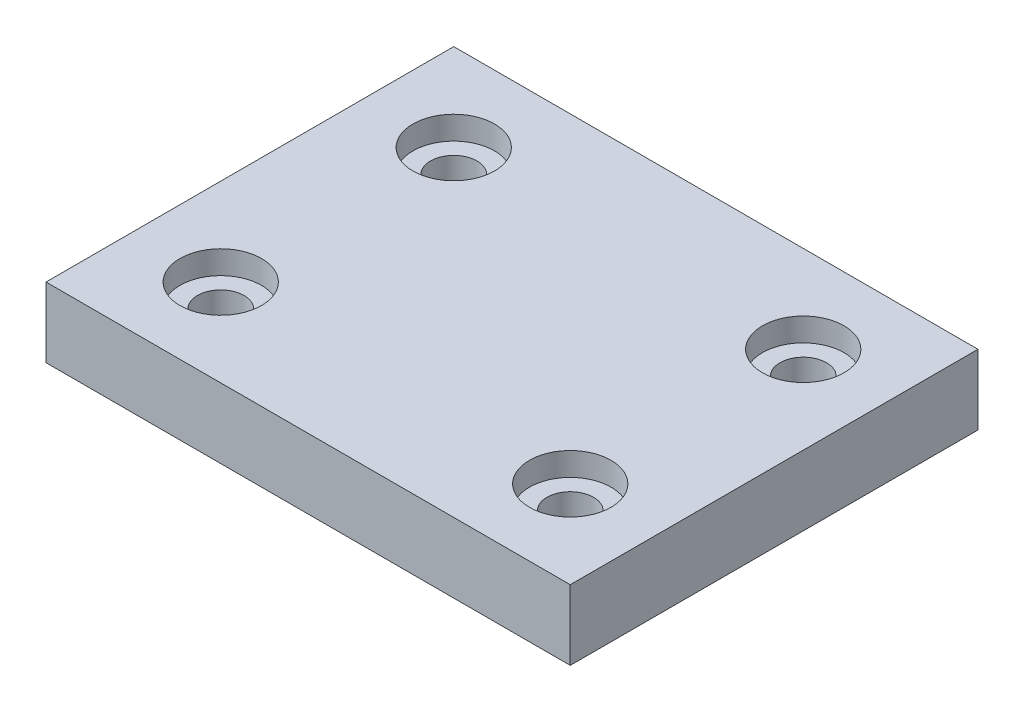
SolidWorks part; units mm, degrees
ref_plane "前视基准面" through (0, 0, 0) normal (0, 0, 1) x (1, 0, 0)
ref_plane "上视基准面" through (0, 0, 0) normal (0, 1, 0) x (1, 0, 0)
ref_plane "右视基准面" through (0, 0, 0) normal (1, 0, 0) x (0, 0, -1)
sketch "草图1" plane through (0, 0, 0) normal (0, 1, 0) x (1, 0, 0)
  line L0 (-45, 35) -> (45, 35)
  line L1 (45, 35) -> (45, -35)
  line L2 (45, -35) -> (-45, -35)
  line L3 (-45, -35) -> (-45, 35)
extrude "凸台-拉伸1" add sketch "草图1" along normal blind 12
ref_plane "基准面1" through (0, 12, 0) normal (0, 1, 0) x (1, 0, 0)
sketch "草图2" plane through (0, 12, 0) normal (0, 1, 0) x (1, 0, 0)
  circle A0 centre (-30, 20) radius 7
  circle A1 centre (30, 20) radius 7
  circle A2 centre (-30, -20) radius 7
  circle A3 centre (30, -20) radius 7
extrude "切除-拉伸1" cut sketch "草图2" against normal blind 4
sketch "草图3" plane through (0, 12, 0) normal (0, 1, 0) x (1, 0, 0)
  circle A0 centre (-30, 20) radius 4
  circle A1 centre (30, 20) radius 4
  circle A2 centre (-30, -20) radius 4
  circle A3 centre (30, -20) radius 4
extrude "切除-拉伸2" cut sketch "草图3" against normal through all
